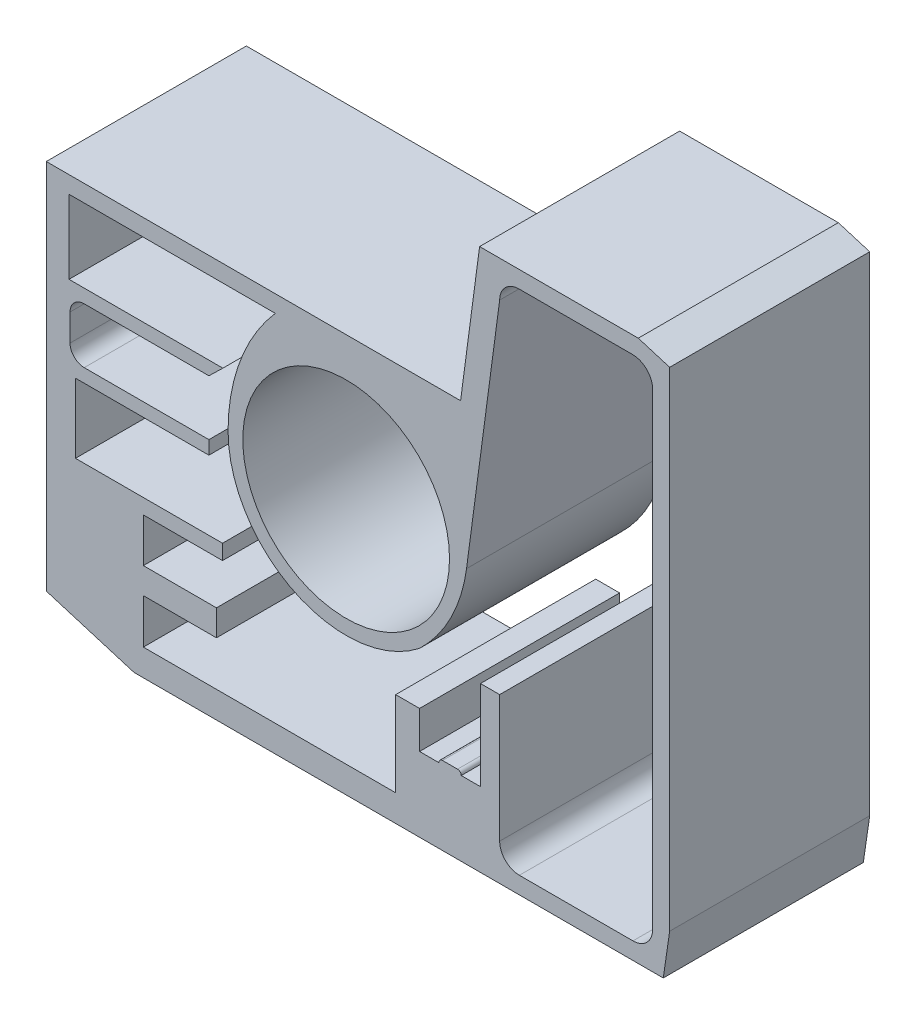
SolidWorks part; units mm, degrees
ref_plane "Alzado" through (0, 0, 0) normal (0, 0, 1) x (1, 0, 0)
ref_plane "Planta" through (0, 0, 0) normal (0, 1, 0) x (1, 0, 0)
ref_plane "Vista lateral" through (0, 0, 0) normal (1, 0, 0) x (0, 0, -1)
sketch "Croquis1" plane through (0, 0, 0) normal (0, 0, 1) x (1, 0, 0)
  line L0 (30.1497, -32.6511) -> (30.1497, -31.3511) construction
  line L1 (47.3997, -32.6511) -> (43.1497, -32.6511) construction
  line L2 (43.1497, -32.6511) -> (43.1497, -31.3511) construction
  line L3 (25.8997, -32.6511) -> (30.1497, -32.6511) construction
  line L6 (39.3111, -62.8734) -> (33.9884, -62.8734)
  line L7 (47.3997, -64.1734) -> (40.6111, -64.1734)
  line L8 (41.3111, -60.8734) -> (31.9884, -60.8734) construction
  line L9 (36.6497, -31.3511) -> (36.6497, -62.8734) construction
  line L18 (25.8997, -32.6511) -> (25.8997, -64.1734) construction
  line L19 (25.8997, -64.1734) -> (32.6884, -64.1734) construction
  line L21 (54.1705, 87.9323) -> (42.48, 0)
  line L25 (32.6884, -64.1734) -> (25.8997, -64.1734)
  line L39 (17.4688, -64.1734) -> (17.4688, -81.0126)
  line L46 (-71.574, -40.6018) -> (-43.6296, -40.6018)
  line L50 (-69.574, -54.1018) -> (-69.574, -42.6018) construction
  line L51 (-71.574, -56.1018) -> (-71.574, -40.6018)
  line L55 (-71.574, -65.2749) -> (-45.774, -65.2749)
  line L56 (-37.8312, -51.0126) -> (-37.8312, -81.0126) construction
  line L57 (43.1497, -31.3511) -> (30.1497, -31.3511) construction
  line L58 (17.4688, -51.0126) -> (-37.8312, -51.0126) construction
  line L59 (17.4688, -81.0126) -> (17.4688, -51.0126) construction
  line L60 (-71.574, -56.1018) -> (-45.774, -56.1018)
  line L61 (-45.774, -65.2749) -> (-45.774, -56.1018)
  line L62 (-45.774, -67.2749) -> (-68.174, -67.2749) construction
  line L63 (-45.774, -54.1018) -> (-69.574, -54.1018) construction
  line L64 (-71.574, -81.0126) -> (-71.574, -65.2749)
  line L65 (114.1705, 100.742) -> (-105.8295, 100.742) construction
  line L66 (114.1705, 100.742) -> (114.1705, -119.258) construction
  line L67 (114.1705, -119.258) -> (-105.8295, -119.258) construction
  line L68 (-43.6296, -35.2869) -> (-43.6296, -40.6018)
  line L69 (-105.8295, -119.258) -> (-105.8295, 100.742) construction
  line L70 (-48.4406, -6.0282) -> (-92.4406, -6.0282)
  line L71 (-48.4406, 13.4776) -> (-92.4406, 13.4776)
  line L72 (-48.4406, -10.7888) -> (-48.4406, -6.0282)
  line L73 (-43.5087, 18.2773) -> (-48.4406, 13.4776)
  line L74 (-25, 44.2773) -> (-97.8087, 44.2773)
  line L75 (47.3997, -32.6511) -> (47.3997, -64.1734) construction
  line L76 (-95.5305, -10.7888) -> (-95.5296, -35.2888)
  line L77 (-48.4406, -10.7888) -> (-95.5305, -10.7888)
  line L78 (-95.5296, -35.2888) -> (-43.6296, -35.2869)
  line L79 (101.0773, 94.742) -> (60.9802, 94.742)
  line L80 (108.1705, -77.4482) -> (108.1705, 87.6489)
  line L81 (61.1219, -84.3997) -> (101.2191, -84.3997)
  line L82 (54.1705, 87.9323) -> (54.1705, -77.4482) construction
  line L83 (-97.8087, 44.2773) -> (-97.8087, 18.2773)
  line L84 (-97.8087, 18.2773) -> (-43.5087, 18.2773)
  line L85 (-97.4406, 8.4747) -> (-97.4406, -1.0253)
  line L86 (-43.4406, -1.0253) -> (-43.4406, 8.4747) construction
  line L87 (-45.774, -54.1018) -> (-45.774, -67.2749) construction
  line L88 (-45.774, -54.1018) -> (-45.774, -42.6018) construction
  line L89 (-45.774, -42.6018) -> (-69.574, -42.6018) construction
  line L90 (17.4688, -81.0126) -> (-71.574, -81.0126)
  line L91 (114.1705, 97.3856) -> (103.0922, 100.742)
  line L92 (114.1705, 97.3856) -> (114.1705, -74.959)
  line L93 (103.0922, 100.742) -> (47.0922, 100.742)
  line L94 (-105.8295, 50.2773) -> (-25, 50.2773)
  line L95 (-105.8295, 50.2773) -> (-105.8295, -81.0126)
  line L96 (-105.8295, -81.0126) -> (-74.8463, -90.3997)
  line L97 (47.0922, 100.742) -> (40.383, 50.2773)
  line L98 (40.383, 50.2773) -> (-25, 50.2773)
  line L99 (-74.8463, -90.3997) -> (111.9116, -90.3997)
  line L100 (114.1705, -74.959) -> (111.9116, -90.3997)
  line L101 (54.1705, -77.4482) -> (54.1705, -32.6511)
  line L102 (54.1705, -32.6511) -> (47.3997, -32.6511)
  line L103 (47.3997, -32.6511) -> (47.3997, -64.1734)
  line L104 (25.8997, -64.1734) -> (25.8997, -51.0126)
  line L105 (25.8997, -51.0126) -> (17.4688, -51.0126)
  line L106 (17.4688, -51.0126) -> (17.4688, -64.1734)
  arc A11 (60.9802, 94.742) -> (54.1705, 87.9323) centre (60.9802, 87.9323) ccw
  arc A12 (108.1705, 87.6489) -> (101.0773, 94.742) centre (101.0773, 87.6489) ccw
  arc A14 (108.1705, -77.4482) -> (101.2191, -84.3997) centre (101.2191, -77.4482) cw
  arc A15 (61.1219, -84.3997) -> (54.1705, -77.4482) centre (61.1219, -77.4482) cw
  arc A16 (40.6111, -64.1734) -> (39.3111, -62.8734) centre (39.3111, -64.1734) ccw
  arc A17 (42.48, 0) -> (25.8997, -32.6511) centre (-12.3023, 7.2832) cw
  arc A18 (32.6884, -64.1734) -> (33.9884, -62.8734) centre (33.9884, -64.1734) cw
  arc A19 (25.8997, -32.6511) -> (-41.676, 0) centre (0, 0) cw
  circle A20 centre (0, 0) radius 36.48
  arc A21 (-25, 44.2773) -> (-41.676, 0) centre (25.4435, 0) ccw
  arc A22 (-92.4406, 13.4776) -> (-97.4406, 8.4747) centre (-92.4406, 8.4776) ccw
  arc A23 (-43.4406, 8.4747) -> (-48.4406, 13.4776) centre (-48.4406, 8.4776) ccw construction
  arc A24 (-48.4406, -6.0282) -> (-43.4406, -1.0253) centre (-48.4406, -1.0282) ccw construction
  arc A25 (-97.4406, -1.0253) -> (-92.4406, -6.0282) centre (-92.4406, -1.0282) ccw
  point P12 (36.6497, -60.8734)
  point P15 (36.48, 0)
  point P55 (-36.48, 0)
  dimension "D2" = 2
  dimension "D5" = 2
  dimension "D7" = 220
  dimension "D11" = 72.8087
  dimension "D25" = 9.1731
  dimension "D41" = 5.3227
  dimension "D12" = 26
  dimension "D49" = 13
  dimension "D55" = 54
  dimension "D16" = 5
  dimension "D32" = 72.96
  dimension "D33" = 44.7972
  dimension "D42" = 1.3
  dimension "D45" = 6.9514
  dimension "D3" = 6
  dimension "D4" = 2
  dimension "D6" = 2
  dimension "D8" = 6
  dimension "D9" = 6
  dimension "D10" = 25
  dimension "D13" = 54.3
  dimension "D14" = 44
  dimension "D15" = 44.222
  dimension "D17" = 9.5
  dimension "D18" = 4.7606
  dimension "D19" = 47.0899
  dimension "D20" = 24.5
  dimension "D21" = 51.9
  dimension "D22" = 5.3149
  dimension "D23" = 27.9444
  dimension "D24" = 15.5
  dimension "D26" = 5.196
  dimension "D27" = 11.5
  dimension "D28" = 23.8
  dimension "D29" = 12.3023
  dimension "D30" = 7.2832
  dimension "D31" = 25.4435
  dimension "D34" = 88.706
  dimension "D35" = 51.0126
  dimension "D36" = 55.3
  dimension "D37" = 89.0427
  dimension "D38" = 15.7377
  dimension "D39" = 16.8392
  dimension "D40" = 15.2196
  dimension "D43" = 165.0971
  dimension "D44" = 40.0971
  dimension "D46" = 8.431
  dimension "D47" = 31.5223
  dimension "D48" = 1.3
  dimension "D50" = 21.5
  dimension "D52" = 40.0971
  dimension "D53" = 9.3227
  dimension "D54" = 22.4
  dimension "D57" = 16.855
  dimension "D58" = 172.3447
  dimension "D59" = 56
  dimension "D60" = 6
  dimension "D61" = 106.855
  dimension "D62" = 6
  dimension "D63" = 186.7579
  dimension "D64" = 11.5755
extrude "Saliente-Extruir1" add sketch "Croquis1" along normal mid plane 70.6
